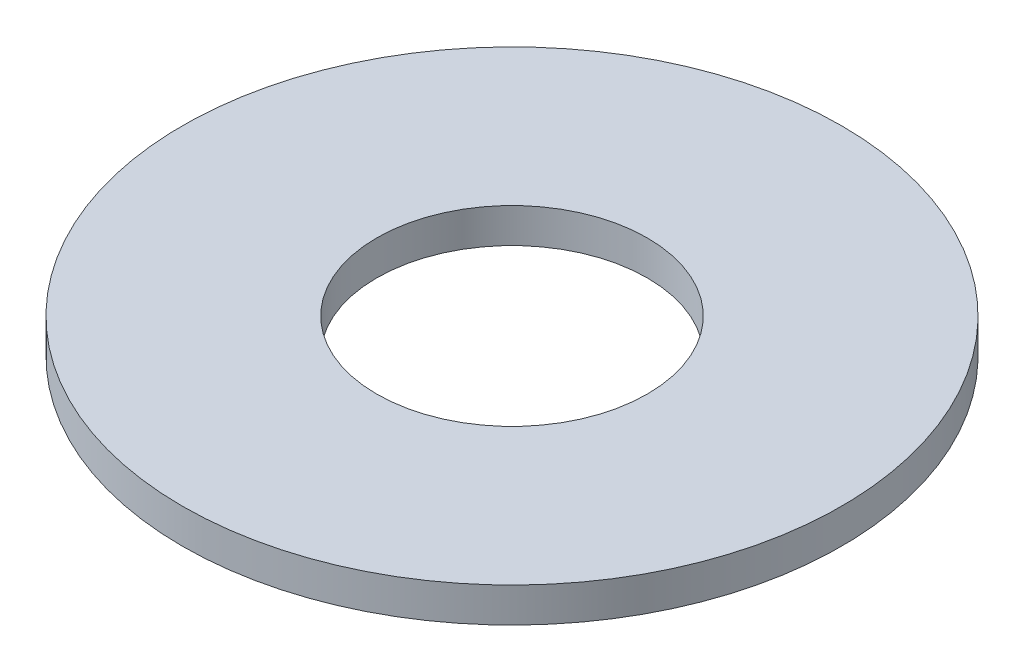
SolidWorks part; units mm, degrees
ref_plane "Front Plane" through (0, 0, 0) normal (0, 0, 1) x (1, 0, 0)
ref_plane "Top Plane" through (0, 0, 0) normal (0, 1, 0) x (1, 0, 0)
ref_plane "Right Plane" through (0, 0, 0) normal (1, 0, 0) x (0, 0, -1)
sketch "Sketch1" plane through (0, 0, 0) normal (0, 1, 0) x (1, 0, 0)
  circle A0 centre (0, 0) radius 38
  circle A1 centre (0, 0) radius 15.6
  dimension "D1" = 31.2
  dimension "D2" = 76
extrude "Boss-Extrude1" add sketch "Sketch1" along normal blind 4
